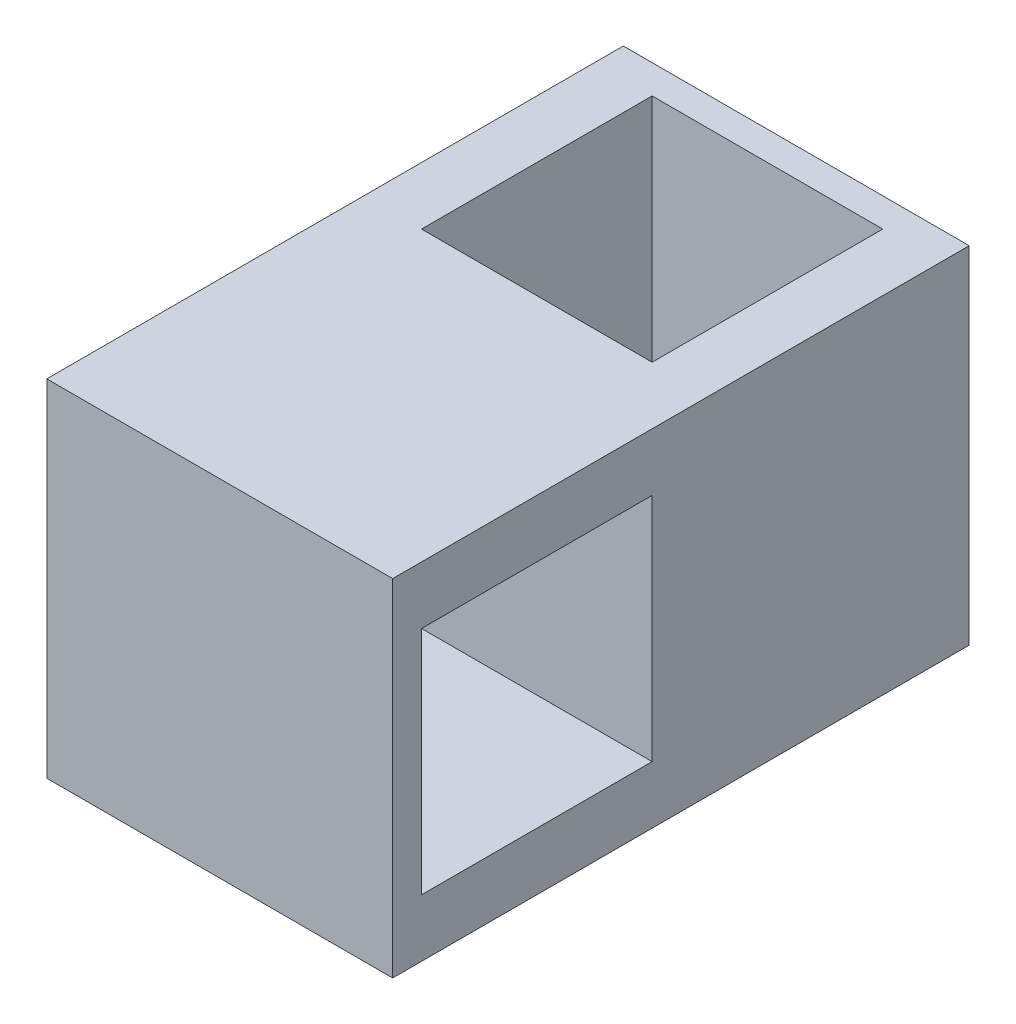
SolidWorks part; units mm, degrees
ref_plane "Front Plane" through (0, 0, 0) normal (0, 0, 1) x (1, 0, 0)
ref_plane "Top Plane" through (0, 0, 0) normal (0, 1, 0) x (1, 0, 0)
ref_plane "Right Plane" through (0, 0, 0) normal (1, 0, 0) x (0, 0, -1)
sketch "Sketch1" plane through (0, 0, 0) normal (0, 0, 1) x (1, 0, 0)
  line L1 (15, -15) -> (-15, -15)
  line L2 (15, -15) -> (15, 15)
  line L3 (15, 15) -> (-15, 15)
  line L4 (-15, -15) -> (-15, 15)
  line L5 (15, -15) -> (-15, 15) construction
  line L6 (15, 15) -> (-15, -15) construction
  point P0 (0, 0)
  dimension "D1" = 30
  dimension "D2" = 30
extrude "Boss-Extrude1" add sketch "Sketch1" along normal blind 50
sketch "Sketch3" plane through (-15, 0, 0) normal (-1, 0, 0) x (0, 0, 1)
  line L0 (25, 15) -> (25, -15)
  line L1 (50, 15) -> (0, 15) construction
  line L2 (50, -15) -> (0, -15) construction
  line L7 (47.5, -10) -> (27.5, -10)
  line L8 (47.5, -10) -> (47.5, 10)
  line L9 (47.5, 10) -> (27.5, 10)
  line L10 (27.5, -10) -> (27.5, 10)
  line L11 (47.5, -10) -> (27.5, 10) construction
  line L12 (47.5, 10) -> (27.5, -10) construction
  point P10 (37.5, 0)
  dimension "D1" = 20
  dimension "D2" = 20
extrude "Cut-Extrude1" cut sketch "Sketch3" against normal through all contours L10 L7 L8 L9
sketch "Sketch4" plane through (0, 15, 0) normal (0, 1, 0) x (1, 0, 0)
  line L0 (15, -25) -> (-15, -25)
  line L1 (15, -50) -> (15, 0) construction
  line L2 (-15, -50) -> (-15, 0) construction
  line L3 (15, 0) -> (-15, 0) construction
  line L6 (10, -22.5) -> (-10, -22.5)
  line L7 (10, -22.5) -> (10, -2.5)
  line L8 (10, -2.5) -> (-10, -2.5)
  line L9 (-10, -22.5) -> (-10, -2.5)
  line L10 (10, -22.5) -> (-10, -2.5) construction
  line L11 (10, -2.5) -> (-10, -22.5) construction
  point P9 (0, -12.5)
  dimension "D1" = 20
  dimension "D2" = 20
  dimension "D3" = 2.5
  dimension "D4" = 5
extrude "Cut-Extrude2" cut sketch "Sketch4" against normal through all contours L9 L6 L7 L8
